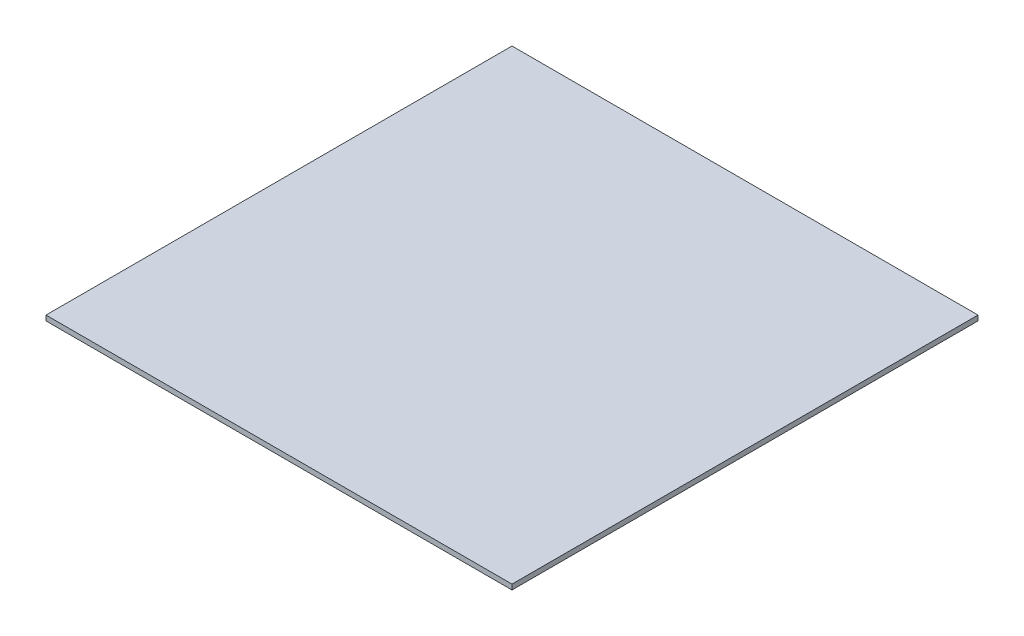
SolidWorks part; units mm, degrees
material "Glass"
ref_plane "Front Plane" through (0, 0, 0) normal (0, 0, 1) x (1, 0, 0)
ref_plane "Top Plane" through (0, 0, 0) normal (0, 1, 0) x (1, 0, 0)
ref_plane "Right Plane" through (0, 0, 0) normal (1, 0, 0) x (0, 0, -1)
sketch "Sketch1" plane through (0, 0, 0) normal (0, 1, 0) x (1, 0, 0)
  line L1 (145, -145) -> (-145, -145)
  line L2 (145, -145) -> (145, 145)
  line L3 (145, 145) -> (-145, 145)
  line L4 (-145, -145) -> (-145, 145)
  line L5 (145, -145) -> (-145, 145) construction
  line L6 (145, 145) -> (-145, -145) construction
  point P0 (0, 0)
  dimension "D1" = 290
extrude "Boss-Extrude1" add sketch "Sketch1" along normal mid plane 3.175
